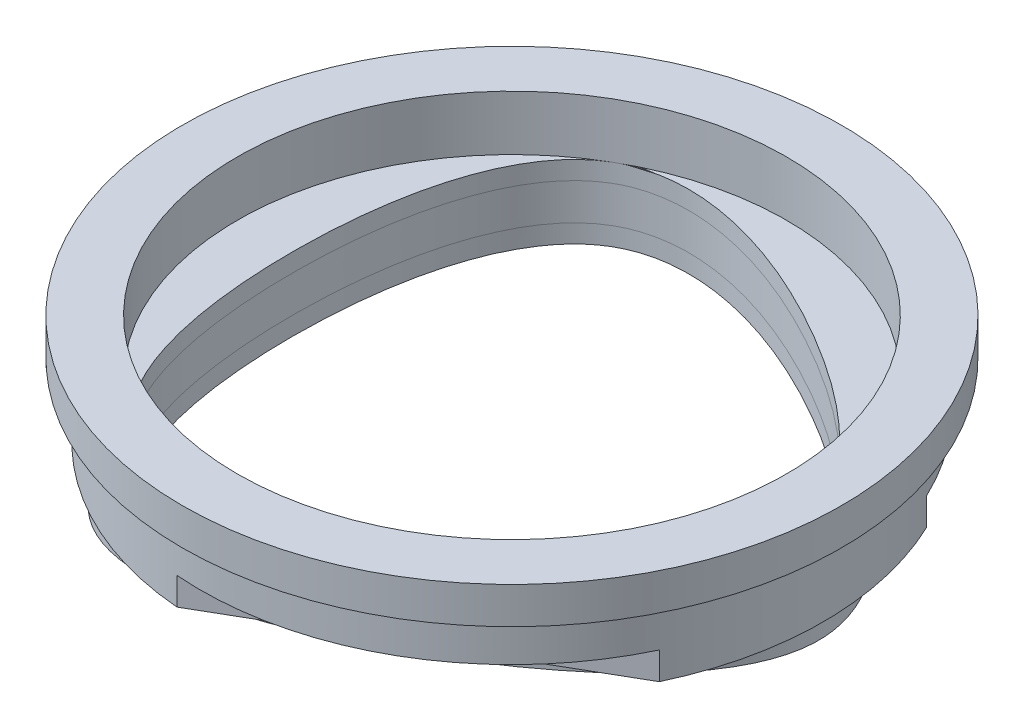
SolidWorks part; units mm, degrees
ref_plane "前视基准面" through (0, 0, 0) normal (0, 0, 1) x (1, 0, 0)
ref_plane "上视基准面" through (0, 0, 0) normal (0, 1, 0) x (1, 0, 0)
ref_plane "右视基准面" through (0, 0, 0) normal (1, 0, 0) x (0, 0, -1)
sketch "草图1" plane through (0, 0, 0) normal (0, 1, 0) x (1, 0, 0)
  line L0 (-180, 0) -> (180, 0)
  line L1 (90, -155.8846) -> (-90, 155.8846)
  line L2 (-90, -155.8846) -> (90, 155.8846)
  circle A3 centre (0, 0) radius 150 construction
  circle A4 centre (75, 129.9038) radius 17.5
  circle A5 centre (-75, 129.9038) radius 17.5
  circle A6 centre (150, 0) radius 17.5
  circle A7 centre (-150, 0) radius 17.5
  circle A8 centre (-75, -129.9038) radius 17.5
  circle A9 centre (75, -129.9038) radius 17.5
  circle A10 centre (0, 0) radius 120
  circle A11 centre (75, 129.9038) radius 30
  circle A12 centre (-75, 129.9038) radius 30
  circle A13 centre (-150, 0) radius 30
  circle A14 centre (-75, -129.9038) radius 30
  circle A15 centre (75, -129.9038) radius 30
  circle A16 centre (150, 0) radius 30
  spline S0 degree 3 poles (-145, 0) (-107.5, -186.1955) (72.5, -125.5737) (215, 0) (72.5, 125.5737) (-107.5, 186.1955) (-145, 0) (-107.5, -186.1955) (72.5, -125.5737) knots -0.5 -0.333333 -0.166667 0 0.166667 0.333333 0.5 0.666667 0.833333 1 1.166667 1.333333 1.5 only from (-83.75, -145.0593) to (-83.75, -145.0593)
  spline S1 degree 3 poles (-96, 166.2769) (66, 114.3154) (192, 0) (66, -114.3154) (-96, -166.2769) (-132, 0) (-96, 166.2769) (66, 114.3154) (192, 0) knots -0.5 -0.333333 -0.166667 0 0.166667 0.333333 0.5 0.666667 0.833333 1 1.166667 1.333333 1.5 only from (60, 103.923) to (60, 103.923)
  point P25 (0, 0)
  point P27 (-66.25, -114.7484)
  point P29 (0, 0)
  point P32 (0, 0)
  point P33 (-132.5, 0)
  point P34 (-167.5, 0)
  point P35 (-66.25, 114.7484)
  point P36 (-83.75, 145.0593)
  point P37 (66.25, 114.7484)
  point P38 (83.75, 145.0593)
  point P39 (132.5, 0)
  point P40 (167.5, 0)
  point P41 (83.75, -145.0593)
  point P42 (66.25, -114.7484)
  point P43 (-83.75, -145.0593)
  point P45 (60, 103.923)
  point P47 (120, 0)
  point P49 (60, -103.923)
  point P51 (-60, -103.923)
  point P53 (-120, 0)
  point P54 (-60, 103.923)
  dimension "D1" = 300
  dimension "D2" = 60
  dimension "D3" = 35
  dimension "D4" = 35
  dimension "D5" = 35
  dimension "D6" = 35
  dimension "D7" = 35
  dimension "D8" = 35
  dimension "D9" = 240
  dimension "D10" = 60
  dimension "D11" = 60
sketch "草图2" plane through (0, 0, 0) normal (0, 1, 0) x (1, 0, 0)
  spline S0 degree 3 poles (-107.5, 186.1955) (72.5, 125.5737) (215, 0) (72.5, -125.5737) (-107.5, -186.1955) (-145, 0) (-107.5, 186.1955) (72.5, 125.5737) (215, 0) knots -0.5 -0.333333 -0.166667 0 0.166667 0.333333 0.5 0.666667 0.833333 1 1.166667 1.333333 1.5 only from (66.25, 114.7484) to (66.25, 114.7484)
  spline S1 degree 3 poles (-96, 166.2769) (66, 114.3154) (192, 0) (66, -114.3154) (-96, -166.2769) (-132, 0) (-96, 166.2769) (66, 114.3154) (192, 0) knots -0.5 -0.333333 -0.166667 0 0.166667 0.333333 0.5 0.666667 0.833333 1 1.166667 1.333333 1.5 only from (60, 103.923) to (60, 103.923)
extrude "凸台-拉伸1" add sketch "草图2" against normal blind 10
sketch "草图3" plane through (0, 0, 0) normal (0, 1, 0) x (1, 0, 0)
  line L0 (-90, -155.8846) -> (90, 155.8846) construction
  line L1 (-13.5165, 169.4618) -> (153.5165, 73.0253)
  line L2 (-140, -96.4365) -> (-140, 96.4365)
  line L3 (-180, 0) -> (180, 0) construction
  line L4 (153.5165, -73.0253) -> (-13.5165, -169.4618)
  line L5 (90, -155.8846) -> (-90, 155.8846) construction
  arc A2 (-13.5165, 169.4618) -> (-140, 96.4365) centre (0, 0) ccw
  arc A3 (153.5165, -73.0253) -> (153.5165, 73.0253) centre (0, 0) ccw
  arc A4 (-140, -96.4365) -> (-13.5165, -169.4618) centre (0, 0) ccw
  spline S0 degree 3 poles (-132, 0) (-96, 166.2769) (66, 114.3154) (192, 0) (66, -114.3154) (-96, -166.2769) (-132, 0) (-96, 166.2769) (66, 114.3154) knots -0.5 -0.333333 -0.166667 0 0.166667 0.333333 0.5 0.666667 0.833333 1 1.166667 1.333333 1.5 only from (-75, 129.9038) to (-75, 129.9038)
  dimension "D1" = 340
  dimension "D2" = 140
  dimension "D3" = 140
  dimension "D4" = 140
extrude "凸台-拉伸2" add sketch "草图3" along normal blind 20
sketch "草图5" plane through (0, 20, 0) normal (0, 1, 0) x (1, 0, 0)
  line L0 (-265, 0) -> (265, 0)
  line L1 (132.5, 229.4967) -> (-132.5, -229.4967)
  line L2 (-132.5, 229.4967) -> (132.5, -229.4967)
  circle A0 centre (0, 0) radius 240
  circle A1 centre (120, 207.8461) radius 25
  circle A2 centre (-120, 207.8461) radius 25
  circle A3 centre (240, 0) radius 25
  circle A4 centre (120, -207.8461) radius 25
  circle A5 centre (-120, -207.8461) radius 25
  circle A6 centre (-240, 0) radius 25
  point P9 (120, 207.8461)
  point P10 (240, 0)
  point P11 (-120, 207.8461)
  point P12 (-240, 0)
  point P13 (-120, -207.8461)
  point P14 (120, -207.8461)
  dimension "D1" = 480
  dimension "D4" = 50
  dimension "D5" = 50
  dimension "D6" = 50
  dimension "D7" = 50
  dimension "D8" = 50
  dimension "D9" = 50
  dimension "D2" = 60
  dimension "D3" = 60
sketch "草图6" plane through (0, 20, 0) normal (0, 1, 0) x (1, 0, 0)
  line L0 (90, -155.8846) -> (-90, 155.8846) construction
  line L1 (207.8461, -120) -> (-207.8461, 120) construction
  line L2 (207.8461, 120) -> (-207.8461, -120) construction
  line L3 (0, -240) -> (0, 240) construction
  line L4 (-90, -155.8846) -> (90, 155.8846) construction
  line L5 (-180, 0) -> (180, 0) construction
  line L6 (-132.5, 229.4967) -> (132.5, -229.4967) construction
  circle A1 centre (0, 0) radius 240 construction
  circle A2 centre (0, 0) radius 170
  spline S0 degree 3 poles (-132, 0) (-96, -166.2769) (66, -114.3154) (192, 0) (66, 114.3154) (-96, 166.2769) (-132, 0) (-96, -166.2769) (66, -114.3154) knots -0.5 -0.333333 -0.166667 0 0.166667 0.333333 0.5 0.666667 0.833333 1 1.166667 1.333333 1.5 only from (-75, -129.9038) to (-75, -129.9038)
  dimension "D4" = 340
  dimension "D1" = 30
  dimension "D2" = 30
  dimension "D3" = 30
extrude "凸台-拉伸3" add sketch "草图6" along normal blind 20
sketch "草图7" plane through (0, 40, 0) normal (0, 1, 0) x (1, 0, 0)
  circle A0 centre (0, 0) radius 150
  circle A1 centre (0, 0) radius 180
extrude "凸台-拉伸4" add sketch "草图7" along normal blind 20
sketch "草图8" plane through (0, 20, 0) normal (0, -1, 0) x (1, 0, 0)
  line L4 (-13.5165, 169.4618) -> (153.5165, 73.0253)
  line L5 (-140, 96.4365) -> (-140, -96.4365)
  line L6 (-13.5165, -169.4618) -> (153.5165, -73.0253)
  arc A3 (-140, 96.4365) -> (-140, -96.4365) centre (0, 0) ccw
  arc A4 (-13.5165, -169.4618) -> (153.5165, -73.0253) centre (0, 0) ccw
  arc A5 (153.5165, 73.0253) -> (-13.5165, 169.4618) centre (0, 0) ccw
extrude "凸台-拉伸5" add sketch "草图8" along normal blind 5
sketch "草图9" plane through (0, 40, 0) normal (0, 1, 0) x (1, 0, 0)
  circle A0 centre (0, 0) radius 150
  dimension "D1" = 300
extrude "切除-拉伸1" cut sketch "草图9" against normal blind 10
